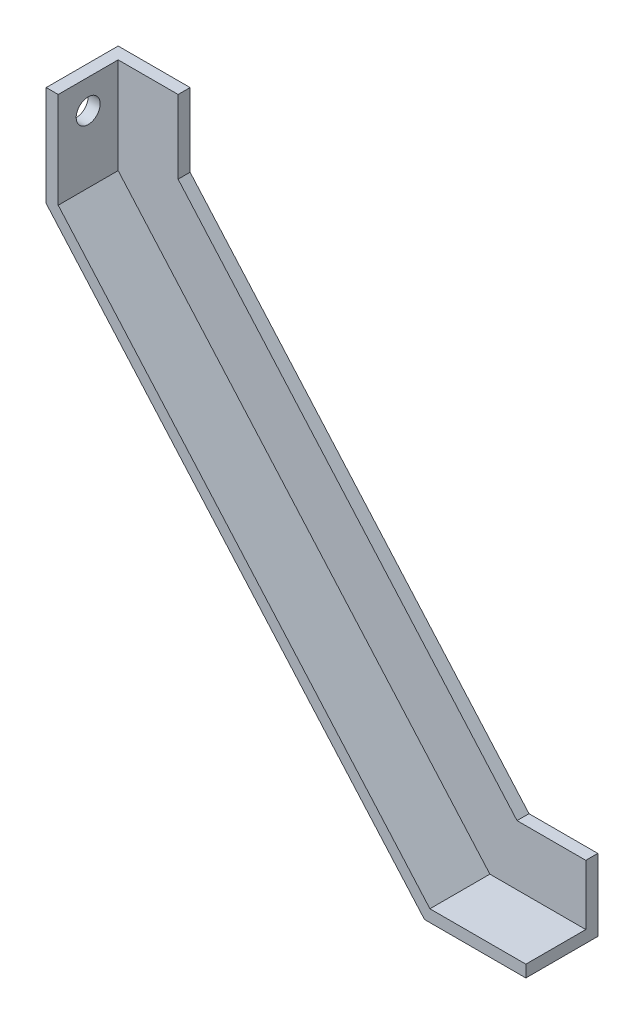
SolidWorks part; units mm, degrees
material "AISI 1010 Steel, hot rolled bar"
ref_plane "Front" through (0, 0, 0) normal (0, 0, 1) x (1, 0, 0)
ref_plane "Top" through (0, 0, 0) normal (0, 1, 0) x (1, 0, 0)
ref_plane "Right" through (0, 0, 0) normal (1, 0, 0) x (0, 0, -1)
sketch "Sketch1" plane through (0, 0, 0) normal (0, 0, 1) x (1, 0, 0)
  line L0 (0, 0) -> (0, -26.5959)
  line L1 (0, -26.5959) -> (100.1624, -140.6925)
  line L2 (100.1624, -140.6925) -> (127, -140.6925)
  line L3 (127, -140.6925) -> (127, -137.5175)
  line L4 (127, -137.5175) -> (101.6, -137.5175)
  line L5 (101.6, -137.5175) -> (3.175, -25.4)
  line L6 (3.175, -25.4) -> (3.175, 0)
  line L7 (3.175, 0) -> (0, 0)
  line L8 (101.6, -137.5175) -> (100.1624, -140.6925) construction
  line L9 (0, -26.5959) -> (3.175, -25.4) construction
  dimension "D1" = 3.175
  dimension "D2" = 3.175
  dimension "D3" = 3.175
  dimension "D4" = 140.6925
  dimension "D5" = 127
  dimension "D6" = 25.4
  dimension "D7" = 25.4
extrude "Boss-Extrude1" add sketch "Sketch1" along normal blind 19.05
sketch "Sketch2" plane through (0, 0, 0) normal (0, 0, -1) x (-1, 0, 0)
  line L0 (-127, -137.5175) -> (-127, -121.6425)
  line L1 (-127, -121.6425) -> (-108.788, -121.6425)
  line L2 (-108.788, -121.6425) -> (-19.05, -19.4205)
  line L3 (-19.05, -19.4205) -> (-19.05, 0)
  line L4 (-19.05, 0) -> (-3.175, 0)
  line L5 (-3.175, 0) -> (-3.175, -25.4)
  line L6 (-3.175, -25.4) -> (-101.6, -137.5175)
  line L15 (0, 0) -> (-3.175, 0)
  line L16 (-3.175, 0) -> (-3.175, -25.4)
  line L17 (-3.175, -25.4) -> (-101.6, -137.5175)
  line L18 (-101.6, -137.5175) -> (-127, -137.5175)
  line L19 (-127, -137.5175) -> (-127, -140.6925)
  line L20 (-127, -140.6925) -> (-100.1624, -140.6925)
  line L21 (-100.1624, -140.6925) -> (0, -26.5959)
  line L22 (0, -26.5959) -> (0, 0)
  line L24 (-3.175, 0) -> (-3.175, -25.4)
  line L25 (-3.175, -25.4) -> (-101.6, -137.5175)
  line M10 (-3.175, 0) -> (-3.175, -25.4)
  line M11 (-3.175, -25.4) -> (-101.6, -137.5175)
  line M12 (-101.6, -137.5175) -> (-127, -137.5175)
  dimension "D1" = 15.875
  dimension "D2" = 15.875
  dimension "D3" = 15.875
  dimension "D4" = 0
extrude "Boss-Extrude2" add sketch "Sketch2" against normal blind 3.175 contours L4 L3 L2 L1 L0 M12 M11 M10
sketch "Sketch3" plane through (3.175, 0, 0) normal (1, 0, 0) x (0, 0, -1)
  line L0 (-19.05, -25.4) -> (-19.05, 0) construction
  line L1 (-19.05, -140.6925) -> (0, -140.6925) construction
  circle A0 centre (-11.1125, -7.6907) radius 3.175
  dimension "D1" = 6.35
  dimension "D2" = 7.9375
  dimension "D3" = 133.0018
extrude "Cut-Extrude1" cut sketch "Sketch3" against normal through all
